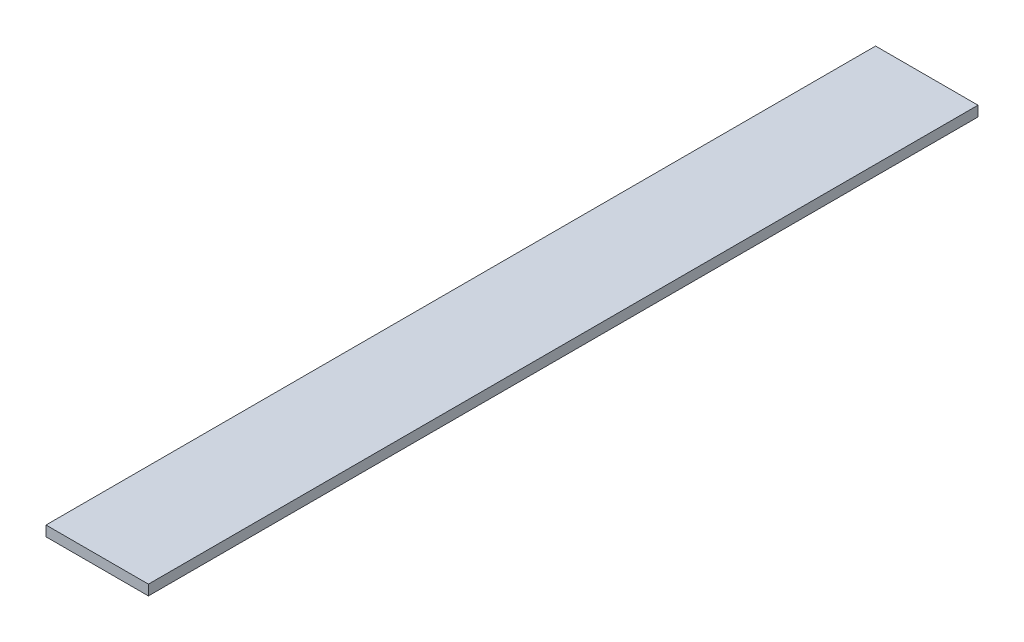
SolidWorks part; units mm, degrees
ref_plane "Front Plane" through (0, 0, 0) normal (0, 0, 1) x (1, 0, 0)
ref_plane "Top Plane" through (0, 0, 0) normal (0, 1, 0) x (1, 0, 0)
ref_plane "Right Plane" through (0, 0, 0) normal (1, 0, 0) x (0, 0, -1)
sketch "Sketch1" plane through (0, 0, 0) normal (0, 1, 0) x (1, 0, 0)
  line L1 (-25, -202.5) -> (25, -202.5)
  line L2 (-25, -202.5) -> (-25, 202.5)
  line L3 (-25, 202.5) -> (25, 202.5)
  line L4 (25, -202.5) -> (25, 202.5)
  line L5 (-25, -202.5) -> (25, 202.5) construction
  line L6 (-25, 202.5) -> (25, -202.5) construction
  point P0 (0, 0)
  dimension "D1" = 50
  dimension "D2" = 405
extrude "Extrude1" add sketch "Sketch1" along normal blind 5
